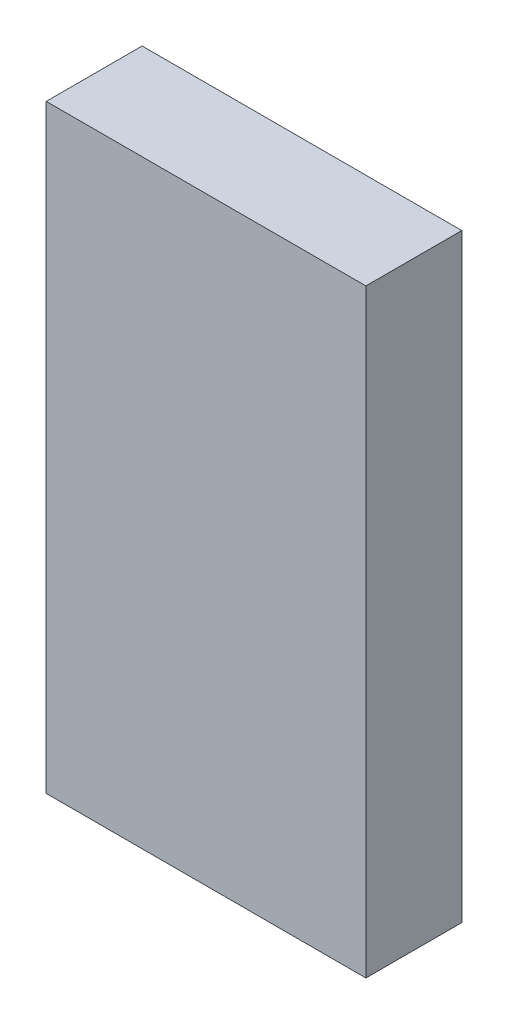
SolidWorks part; units mm, degrees
ref_plane "Front Plane" through (0, 0, 0) normal (0, 0, 1) x (1, 0, 0)
ref_plane "Top Plane" through (0, 0, 0) normal (0, 1, 0) x (1, 0, 0)
ref_plane "Right Plane" through (0, 0, 0) normal (1, 0, 0) x (0, 0, -1)
sketch "Sketch1" plane through (0, 0, 0) normal (0, 1, 0) x (1, 0, 0)
  line L1 (-20, 6) -> (20, 6)
  line L2 (-20, 6) -> (-20, -6)
  line L3 (-20, -6) -> (20, -6)
  line L4 (20, 6) -> (20, -6)
  line L5 (-20, 6) -> (20, -6) construction
  line L6 (-20, -6) -> (20, 6) construction
  point P0 (0, 0)
  dimension "D1" = 12
  dimension "D2" = 40
extrude "Boss-Extrude1" add sketch "Sketch1" along normal mid plane 75
scale "25% Scale" bodies to scale 101 scale about centroid uniform scaling yes scale factor 0.25
